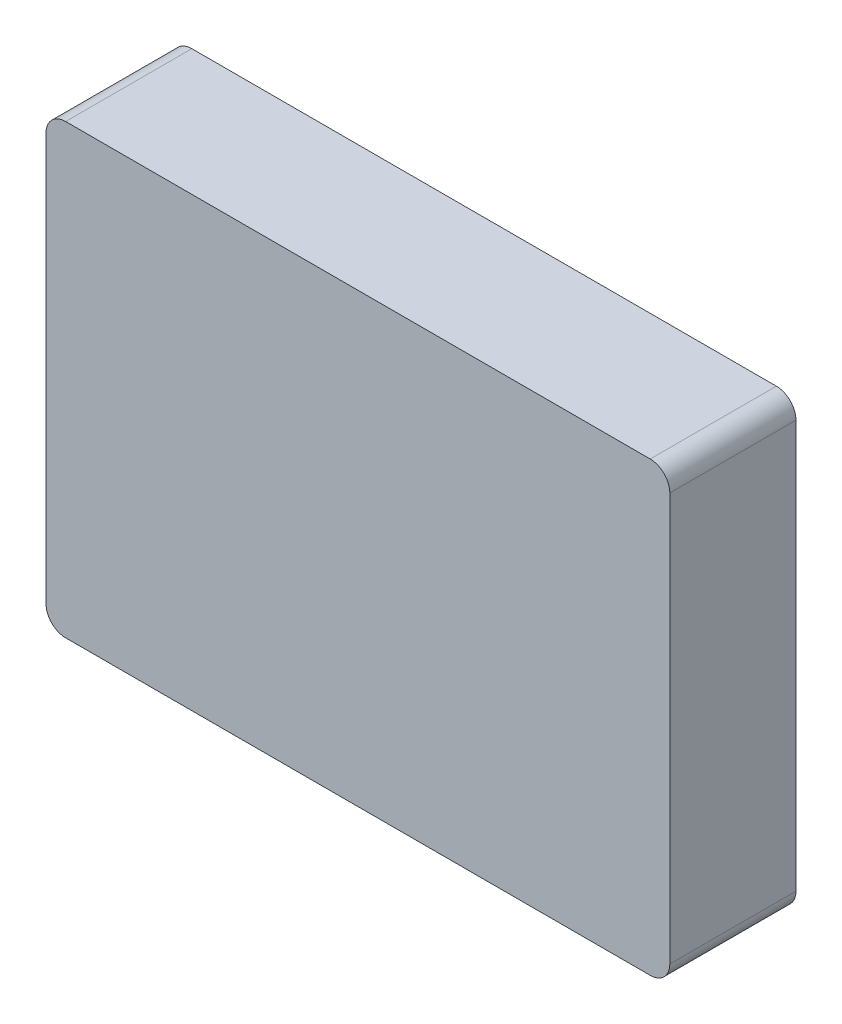
SolidWorks part; units mm, degrees
ref_plane "Front" through (0, 0, 0) normal (0, 0, 1) x (1, 0, 0)
ref_plane "Top" through (0, 0, 0) normal (0, 1, 0) x (1, 0, 0)
ref_plane "Right" through (0, 0, 0) normal (1, 0, 0) x (0, 0, -1)
sketch "Sketch1" plane through (0, 0, 0) normal (0, 0, 1) x (1, 0, 0)
  line L1 (-41.7, -31.9) -> (41.7, -31.9)
  line L2 (-44.5, -29.1) -> (-44.5, 29.1)
  line L3 (-41.7, 31.9) -> (41.7, 31.9)
  line L4 (44.5, -29.1) -> (44.5, 29.1)
  line L5 (-44.5, -31.9) -> (44.5, 31.9) construction
  line L6 (-44.5, 31.9) -> (44.5, -31.9) construction
  arc A0 (-41.7, -31.9) -> (-44.5, -29.1) centre (-41.7, -29.1) cw
  arc A1 (41.7, -31.9) -> (44.5, -29.1) centre (41.7, -29.1) ccw
  arc A2 (41.7, 31.9) -> (44.5, 29.1) centre (41.7, 29.1) cw
  arc A3 (-44.5, 29.1) -> (-41.7, 31.9) centre (-41.7, 29.1) cw
  point P0 (0, 0)
  dimension "D3" = 2.8
  dimension "D1" = 89
  dimension "D2" = 63.8
extrude "Boss-Extrude1" add sketch "Sketch1" along normal blind 18
